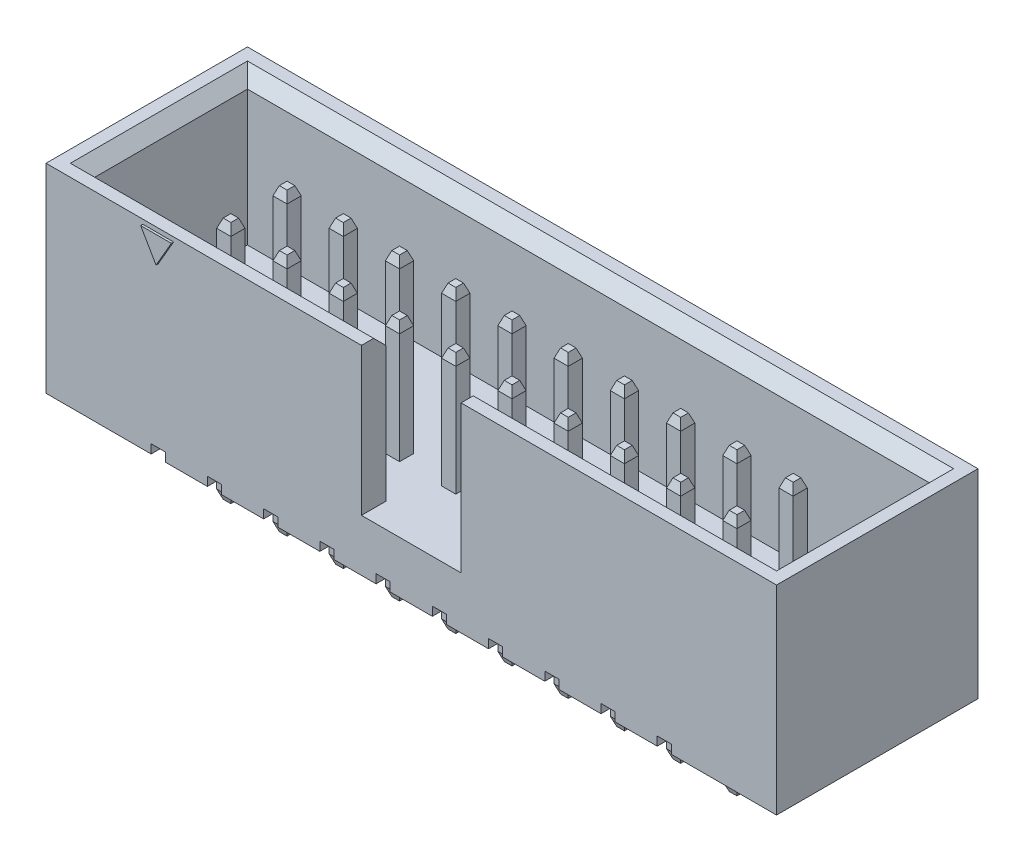
SolidWorks part; units mm, degrees
ref_plane "Front Plane" through (0, 0, 0) normal (0, 0, 1) x (1, 0, 0)
ref_plane "Top Plane" through (0, 0, 0) normal (0, 1, 0) x (1, 0, 0)
ref_plane "Right Plane" through (0, 0, 0) normal (1, 0, 0) x (0, 0, -1)
sketch "Sketch1" plane through (0, 0, 0) normal (0, 1, 0) x (1, 0, 0)
  line L1 (-16.5, -4.55) -> (16.5, -4.55)
  line L2 (-16.5, -4.55) -> (-16.5, 4.55)
  line L3 (-16.5, 4.55) -> (16.5, 4.55)
  line L4 (16.5, -4.55) -> (16.5, 4.55)
  line L5 (-16.5, -4.55) -> (16.5, 4.55) construction
  line L6 (-16.5, 4.55) -> (16.5, -4.55) construction
  point P0 (0, 0)
  dimension "D1" = 33
  dimension "D2" = 9.1
extrude "Boss-Extrude1" add sketch "Sketch1" along normal blind 9
sketch "Sketch2" plane through (0, 9, 0) normal (0, 1, 0) x (1, 0, 0)
  line L0 (15.4, 3.45) -> (16.5, 3.45) construction
  line L1 (-15.4, 3.45) -> (15.4, 3.45)
  line L2 (-15.4, 3.45) -> (-15.4, -3.45)
  line L3 (-15.4, -3.45) -> (15.4, -3.45)
  line L4 (15.4, 3.45) -> (15.4, -3.45)
  line L5 (-15.4, 3.45) -> (15.4, -3.45) construction
  line L6 (-15.4, -3.45) -> (15.4, 3.45) construction
  line L7 (16.5, -4.55) -> (16.5, 4.55) construction
  line L8 (15.4, 3.45) -> (15.4, 4.55) construction
  line L9 (16.5, 4.55) -> (-16.5, 4.55) construction
  point P0 (0, 0)
  dimension "D2" = 30.8
  dimension "D1" = 1.1
extrude "Cut-Extrude1" cut sketch "Sketch2" against normal offset from surface (6.65 mm away) 2.35 up to face at (0, 0, 0)
chamfer "Chamfer2" distance 0.55 angle 45 4 edges at (0, 9, 3.45) (15.4, 9, 0) (0, 9, -3.45) (-15.4, 9, 0)
sketch "Sketch5" plane through (0, 0, 4.55) normal (0, 0, 1) x (1, 0, 0)
  line L0 (-2.25, 2.35) -> (-2.25, 9)
  line L1 (-2.25, 2.35) -> (2.25, 2.35)
  line L2 (-2.25, 9) -> (2.25, 9)
  line L3 (2.25, 2.35) -> (2.25, 9)
  line L4 (-2.25, 2.35) -> (2.25, 9) construction
  line L5 (-2.25, 9) -> (2.25, 2.35) construction
  line L6 (-16.5, 9) -> (16.5, 9) construction
  line L7 (-15.4, 2.35) -> (15.4, 2.35) construction
  point P1 (0, 5.675)
  point P10 (0, 5.675)
  dimension "D1" = 4.5
extrude "Cut-Extrude3" cut sketch "Sketch5" against normal up to next and the other way through all
sketch "Sketch3" plane through (0, 2.35, 0) normal (0, 1, 0) x (1, 0, 0)
  line L0 (-15.4, 3.45) -> (-15.4, -3.45) construction
  line L1 (-11.75, 1.59) -> (-11.11, 1.59)
  line L2 (-11.75, 1.59) -> (-11.75, 0.95)
  line L3 (-11.75, 0.95) -> (-11.11, 0.95)
  line L4 (-11.11, 1.59) -> (-11.11, 0.95)
  line L5 (-11.75, 1.59) -> (-11.11, 0.95) construction
  line L6 (-11.75, 0.95) -> (-11.11, 1.59) construction
  point P0 (-11.43, 1.27)
  dimension "D1" = 0.64
  dimension "D2" = 3.97
  dimension "D3" = 1.27
extrude "Cut-Extrude6" cut sketch "Sketch3" against normal through all
pattern_linear "LPattern9" count 10 spacing 2.54 along (1, 0, 0) count 2 spacing 2.54 along (0, 0, 1) of "Cut-Extrude6"
sketch "Sketch7" plane through (0, 0, 0) normal (0, 1, 0) x (1, 0, 0)
  line L1 (-11.75, 1.59) -> (-11.11, 1.59)
  line L2 (-11.75, 1.59) -> (-11.75, 0.95)
  line L3 (-11.75, 0.95) -> (-11.11, 0.95)
  line L4 (-11.11, 1.59) -> (-11.11, 0.95)
  line L5 (-11.75, 1.59) -> (-11.11, 0.95) construction
  line L6 (-11.75, 0.95) -> (-11.11, 1.59) construction
  point P0 (-11.43, 1.27)
  point P5 (0, 0)
  point P6 (0, 0)
  point P7 (0, 0)
  point P8 (-10.79, 0.95)
  point P9 (-11.43, 1.59)
extrude "Boss-Extrude3" add sketch "Sketch7" along normal blind 7.75 and the other way blind 3.25 separate body
chamfer "Chamfer3" distance 0.4 angle 20 8 edges at (-11.43, -3.25, -1.59) (-11.75, -3.25, -1.27) (-11.43, -3.25, -0.95) (-11.11, -3.25, -1.27) (-11.43, 7.75, -0.95) (-11.75, 7.75, -1.27) (-11.43, 7.75, -1.59) (-11.11, 7.75, -1.27)
pattern_linear "LPattern17" count 10 spacing 2.54 along (1, 0, 0) count 2 spacing 2.54 along (0, 0, 1) of bodies 113
sketch "Sketch6" plane through (0, 0, 4.55) normal (0, 0, 1) x (1, 0, 0)
  line L0 (-16.5, 0) -> (16.5, 0) construction
  line L1 (-11.75, 0) -> (-11.11, 0)
  line L2 (-11.75, 0) -> (-11.75, 0.4)
  line L3 (-11.75, 0.4) -> (-11.11, 0.4)
  line L4 (-11.11, 0) -> (-11.11, 0.4)
  line L5 (-11.75, 0) -> (-11.11, 0.4) construction
  line L6 (-11.75, 0.4) -> (-11.11, 0) construction
  line L7 (-11.11, -2.85) -> (-11.11, 7.35) construction
  line L8 (-11.75, -2.85) -> (-11.75, 7.35) construction
  point P0 (-11.43, 0.2)
  point P8 (-11.995, 0)
  dimension "D2" = 0.4
extrude "Cut-Extrude4" cut sketch "Sketch6" against normal through all
pattern_linear "LPattern2" count 10 spacing 2.54 along (1, 0, 0) of "Cut-Extrude4"
sketch "Sketch4" plane through (0, 0, 4.55) normal (0, 0, 1) x (1, 0, 0)
  line L0 (-12.1228, 8.8) -> (-10.7372, 8.8)
  line L1 (-10.7372, 8.8) -> (-11.43, 7.6)
  line L2 (-11.43, 7.6) -> (-12.1228, 8.8)
  line L3 (-16.5, 9) -> (-2.25, 9) construction
  line L4 (-11.43, 0.4) -> (-11.43, 7.6) construction
  line L6 (-11.11, 0.4) -> (-11.75, 0.4) construction
  dimension "D1" = 1.2
  dimension "D2" = 0.2
extrude "Boss-Extrude2" add sketch "Sketch4" along normal blind 0.1
equation "\"pos\" = 20"
equation "\"D1@Sketch1\" = ( 2.54 * ( \"pos\" / 2 ) + 7.6 )"
equation "\"D2@Sketch2\" = ( 2.54 * ( \"pos\" / 2 ) + 5.4 )"
equation "\"D1@LPattern2\"=\"pos\"/2"
equation "\"D1@LPattern9\"= \"pos\" / 2"
equation "\"D1@LPattern17\"= \"pos\" / 2"
